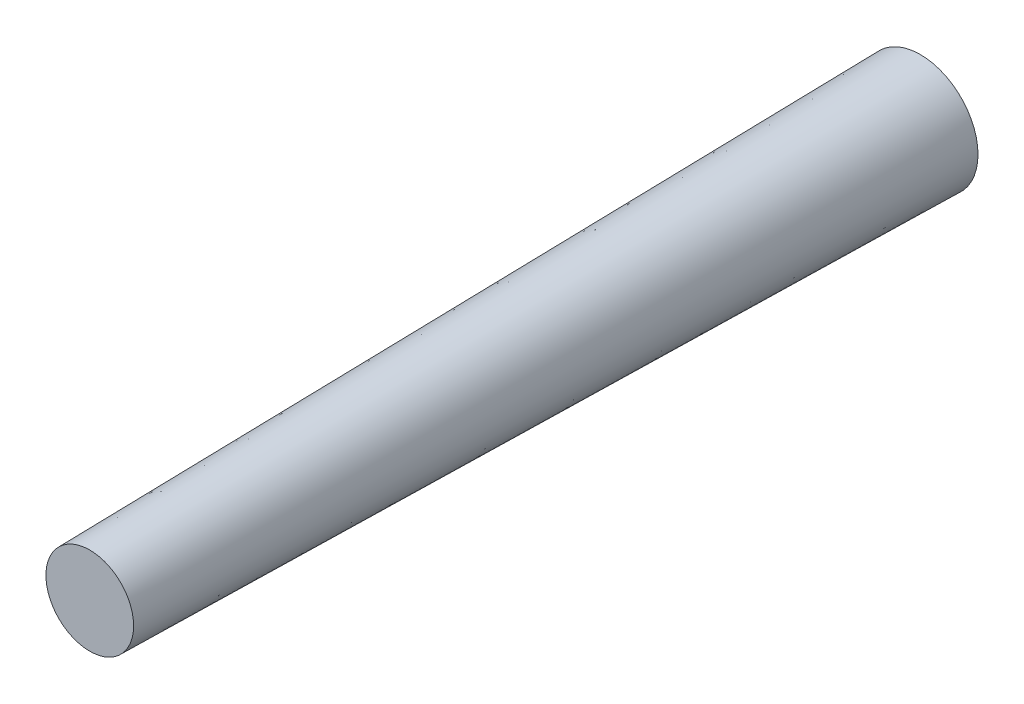
SolidWorks part; units mm, degrees
ref_plane "Front Plane" through (0, 0, 0) normal (0, 0, 1) x (1, 0, 0)
ref_plane "Top Plane" through (0, 0, 0) normal (0, 1, 0) x (1, 0, 0)
ref_plane "Right Plane" through (0, 0, 0) normal (1, 0, 0) x (0, 0, -1)
sketch "Sketch2" plane through (0, 0, 0) normal (0, 0, 1) x (1, 0, 0)
  circle A0 centre (0, 0) radius 2.5
extrude "Boss-Extrude1" add sketch "Sketch2" along normal blind 36 draft 0.954
